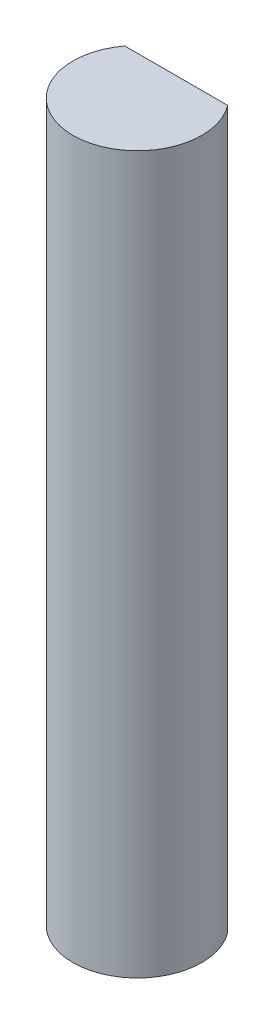
SolidWorks part; units mm, degrees
ref_plane "Plan de face" through (0, 0, 0) normal (0, 0, 1) x (1, 0, 0)
ref_plane "Plan de dessus" through (0, 0, 0) normal (0, 1, 0) x (1, 0, 0)
ref_plane "Plan de droite" through (0, 0, 0) normal (1, 0, 0) x (0, 0, -1)
sketch "Esquisse1" plane through (0, 0, 0) normal (0, 1, 0) x (1, 0, 0)
  circle A0 centre (0, 0) radius 3.15
  dimension "D1" = 6.3
extrude "Boss.-Extru.1" add sketch "Esquisse1" along normal mid plane 35
sketch "Sketch1" plane through (0, 17.5, 0) normal (0, 1, 0) x (1, 0, 0)
  line L0 (-2.5125, 1.9) -> (2.5125, 1.9)
  line L1 (-2.5125, 1.9) -> (-2.5125, 3.4)
  line L2 (-2.5125, 3.4) -> (2.5125, 3.4)
  line L3 (2.5125, 3.4) -> (2.5125, 1.9)
  circle A0 centre (0, 0) radius 3.15 construction
  dimension "D3" = 1.5
  dimension "D1" = 1.9
  dimension "D2" = 1.9
extrude "Cut-Extrude1" cut sketch "Sketch1" against normal up to surface (35 mm away) up to face at (0, -17.5, 3.15)
